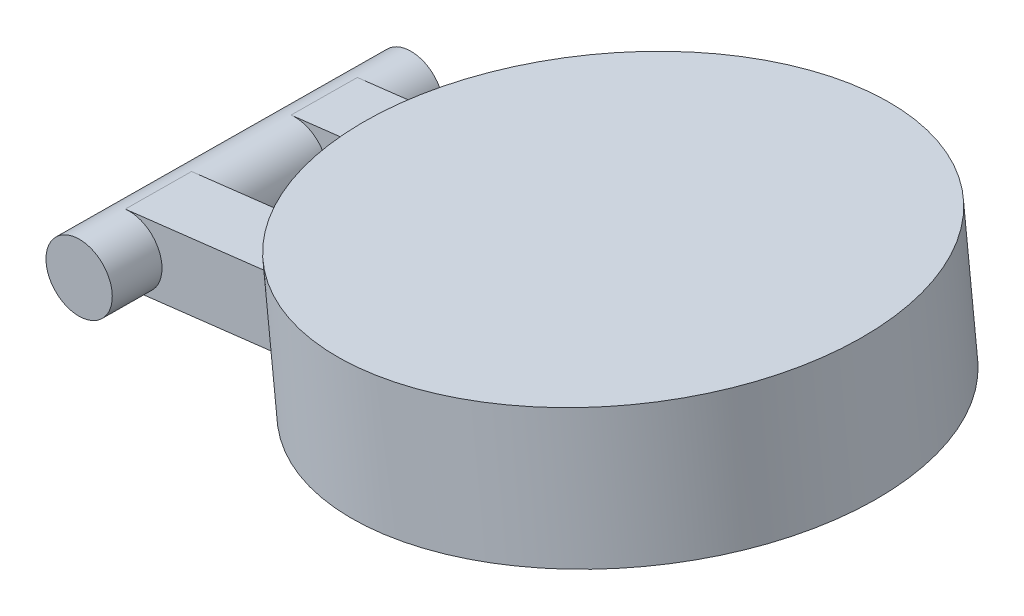
SolidWorks part; units mm, degrees
ref_plane "Alzado" through (0, 0, 0) normal (0, 0, 1) x (1, 0, 0)
ref_plane "Planta" through (0, 0, 0) normal (0, 1, 0) x (1, 0, 0)
ref_plane "Vista lateral" through (0, 0, 0) normal (1, 0, 0) x (0, 0, -1)
sketch "Croquis1" plane through (3.1025, -26.4121, 0.2314) normal (0.1167, -0.9931, 0.0087) x (0.9932, 0.1167, -0.001)
  circle A0 centre (-115.802, 158.9846) radius 15
  dimension "D1" = 30
extrude "Saliente-Extruir1" add sketch "Croquis1" along normal blind 8
sketch "Croquis2" plane through (4.0358, -34.3571, 0.301) normal (0.1167, -0.9931, 0.0087) x (0.9932, 0.1167, -0.001)
  line L0 (-115.802, 168.9846) -> (-115.802, 148.9846) construction
  circle A0 centre (-115.802, 158.9846) radius 4
  circle A1 centre (-115.802, 168.9846) radius 1.5
  circle A2 centre (-115.802, 148.9846) radius 1.5
  dimension "D2" = 3
  dimension "D3" = 8
  dimension "D1" = 20
extrude "Cortar-Extruir1" cut sketch "Croquis2" against normal blind 3
sketch "Croquis3" plane through (4.0358, -34.3571, 0.301) normal (0.1167, -0.9931, 0.0087) x (0.9932, 0.1167, -0.001)
  line L0 (-115.802, 158.9846) -> (-140.802, 158.9846) construction
  line L1 (-115.802, 163.9846) -> (-140.802, 163.9846) construction
  line L2 (-115.802, 153.9846) -> (-140.802, 153.9846) construction
  line L3 (-115.802, 155.9846) -> (-140.802, 155.9846)
  line L4 (-115.802, 165.9846) -> (-140.802, 165.9846)
  line L5 (-115.802, 151.9846) -> (-140.802, 151.9846)
  line L6 (-115.802, 161.9846) -> (-140.802, 161.9846)
  line L7 (-140.802, 165.9846) -> (-140.802, 161.9846)
  line L8 (-140.802, 155.9846) -> (-140.802, 151.9846)
  line L9 (-125.0169, 165.9846) -> (-125.0169, 151.9846)
  circle M4 centre (-115.802, 158.9846) radius 15
  dimension "D1" = 25
  dimension "D2" = 5
  dimension "D3" = 5
extrude "Saliente-Extruir2" add sketch "Croquis3" against normal blind 4 contours L4 L7 L6 M4 | L3 L8 L5 M4 | L9 L3 L5 M4 | L9 L4 L6 M4
ref_plane "Plano1" through (0, 1.3928, 158.9785) normal (0, 0.0088, 1) x (1, 0, 0)
sketch "Croquis4" plane through (0, 1.3928, 158.9785) normal (0, 0.0088, 1) x (1, 0, 0)
  line L4 (-124.1514, -49.4154) -> (-124.6181, -45.4428)
  line L5 (-124.6181, -45.4428) -> (-136.2715, -46.8116)
  line L6 (-136.2715, -46.8116) -> (-135.8048, -50.7843)
  line L7 (-135.8048, -50.7843) -> (-124.1514, -49.4154)
  line L8 (-124.1514, -49.4154) -> (-124.6181, -45.4428)
  line L9 (-124.6181, -45.4428) -> (-136.2715, -46.8116)
  line L10 (-136.2715, -46.8116) -> (-135.8048, -50.7843)
  line L11 (-135.8048, -50.7843) -> (-124.1514, -49.4154)
  circle A0 centre (-134.0518, -48.5646) radius 2
  dimension "D1" = 0
extrude "Saliente-Extruir3" add sketch "Croquis4" along normal blind 10 and the other way blind 10 contours A0
sketch "Croquis5" plane through (0, 1.4804, 168.9781) normal (0, 0.0088, 1) x (1, 0, 0)
  line L0 (-134.2851, -46.5783) -> (-136.2715, -46.8116) construction
  line L1 (-136.2715, -46.8116) -> (-136.0381, -48.7979) construction
  line L2 (-136.0381, -48.7979) -> (-135.8048, -50.7843) construction
  line L3 (-135.8048, -50.7843) -> (-133.8185, -50.5509) construction
  line L4 (-134.2851, -46.5783) -> (-136.2715, -46.8116)
  line L5 (-136.2715, -46.8116) -> (-136.0381, -48.7979)
  line L6 (-136.0381, -48.7979) -> (-135.8048, -50.7843)
  line L7 (-135.8048, -50.7843) -> (-133.8185, -50.5509)
  line L8 (-134.2851, -46.5783) -> (-134.4795, -44.923)
  line L9 (-134.4795, -44.923) -> (-138.1518, -45.3543)
  line L10 (-138.1518, -45.3543) -> (-137.1921, -53.5251)
  line L11 (-137.1921, -53.5251) -> (-133.5198, -53.0937)
  line L12 (-133.5198, -53.0937) -> (-133.8185, -50.5509)
  arc A0 (-134.2851, -46.5783) -> (-136.0381, -48.7979) centre (-134.0518, -48.5646) ccw construction
  circle A1 centre (-134.0518, -48.5646) radius 2
  circle A2 centre (-134.0518, -48.5646) radius 2
  arc A3 (-136.0381, -48.7979) -> (-133.8185, -50.5509) centre (-134.0518, -48.5646) ccw construction
  arc A4 (-134.2851, -46.5783) -> (-136.0381, -48.7979) centre (-134.0518, -48.5646) ccw
  arc A5 (-136.0381, -48.7979) -> (-133.8185, -50.5509) centre (-134.0518, -48.5646) ccw
  circle M2 centre (-134.0518, -48.5646) radius 2
  dimension "D1" = 0
extrude "Cortar-Extruir2" cut sketch "Croquis5" against normal blind 26 contours L11 L12 L7 L6 L5 L4 L8 L9 L10 | L4 L5 M2 | L6 L7 M2
sketch "Croquis6" plane through (4.0358, -34.3571, 0.301) normal (0.1167, -0.9931, 0.0087) x (0.9932, 0.1167, -0.001)
  line L6 (-101.802, 158.9846) -> (-129.802, 158.9846) construction
  line L7 (-101.802, 159.4846) -> (-129.802, 159.4846)
  line L8 (-101.802, 158.4846) -> (-129.802, 158.4846)
  line L9 (-137.802, 154.9846) -> (-137.802, 152.9846)
  line L10 (-137.802, 154.9846) -> (-137.802, 152.9846)
  line L11 (-137.802, 152.9846) -> (-128.4511, 152.9846)
  line L12 (-137.802, 152.9846) -> (-128.4511, 152.9846)
  line L13 (-128.4511, 164.9846) -> (-137.802, 164.9846)
  line L14 (-128.4511, 164.9846) -> (-137.802, 164.9846)
  line L15 (-137.802, 164.9846) -> (-137.802, 162.9846)
  line L16 (-137.802, 164.9846) -> (-137.802, 162.9846)
  line L17 (-137.802, 162.9846) -> (-129.2184, 162.9846)
  line L18 (-137.802, 162.9846) -> (-129.2184, 162.9846)
  line L19 (-129.2184, 154.9846) -> (-137.802, 154.9846)
  line L20 (-129.2184, 154.9846) -> (-137.802, 154.9846)
  arc A3 (-129.2184, 162.9846) -> (-129.2184, 154.9846) centre (-115.802, 158.9846) ccw
  arc A4 (-128.4511, 152.9846) -> (-128.4511, 164.9846) centre (-115.802, 158.9846) ccw
  arc A5 (-129.2184, 162.9846) -> (-129.2184, 154.9846) centre (-115.802, 158.9846) ccw
  arc A6 (-128.4511, 152.9846) -> (-128.4511, 164.9846) centre (-115.802, 158.9846) ccw
  circle A8 centre (-115.802, 158.9846) radius 4.5
  circle A9 centre (-115.802, 158.9846) radius 4.5
  dimension "D1" = 1
  dimension "D2" = 0.5
extrude "Cortar-Extruir3" cut sketch "Croquis6" against normal blind 0.5
